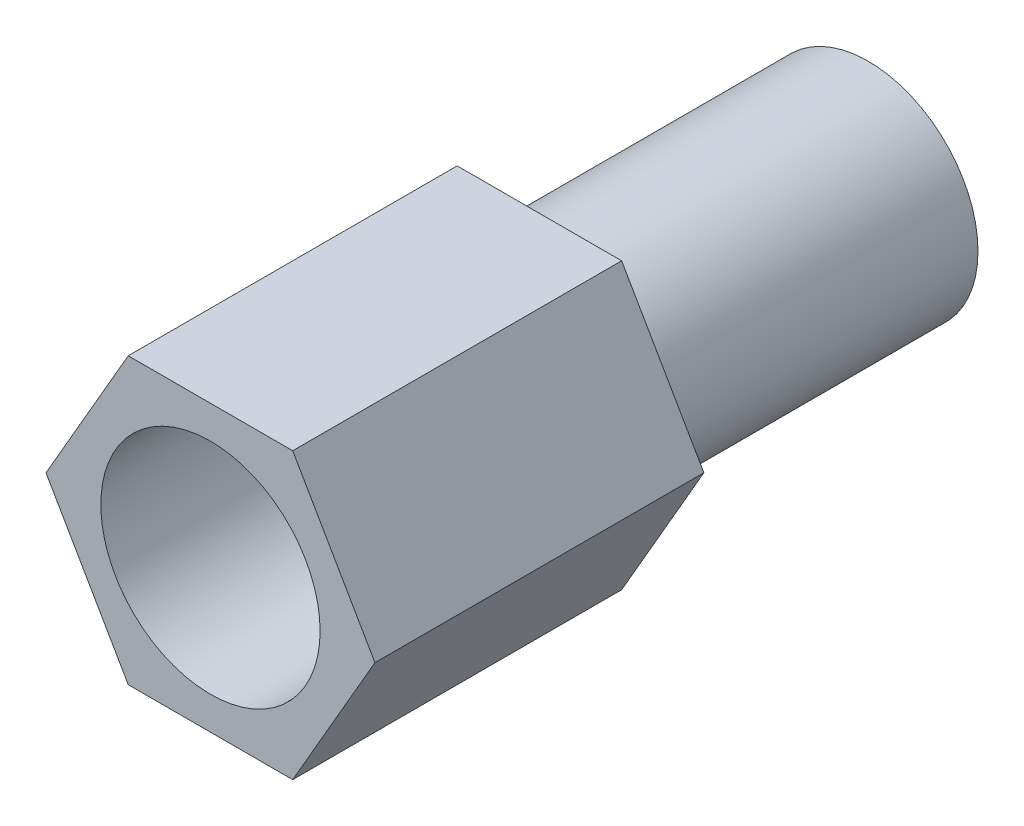
SolidWorks part; units mm, degrees
ref_plane "前视基准面" through (0, 0, 0) normal (0, 0, 1) x (1, 0, 0)
ref_plane "上视基准面" through (0, 0, 0) normal (0, 1, 0) x (1, 0, 0)
ref_plane "右视基准面" through (0, 0, 0) normal (1, 0, 0) x (0, 0, -1)
sketch "草图1" plane through (0, 0, 0) normal (0, 0, 1) x (1, 0, 0)
  line L1 (-1.5, 0) -> (-0.75, -1.299)
  line L2 (-0.75, -1.299) -> (0.75, -1.299)
  line L3 (0.75, -1.299) -> (1.5, 0)
  line L4 (1.5, 0) -> (0.75, 1.299)
  line L5 (0.75, 1.299) -> (-0.75, 1.299)
  line L6 (-0.75, 1.299) -> (-1.5, 0)
  circle A0 centre (0, 0) radius 1.299 construction
  circle A1 centre (0, 0) radius 1
  dimension "D1" = 2
  dimension "D2" = 3
extrude "凸台-拉伸1" add sketch "草图1" along normal blind 3
sketch "草图2" plane through (0, 0, 0) normal (0, 0, 1) x (1, 0, 0)
  circle A0 centre (0, 0) radius 1
extrude "凸台-拉伸2" add sketch "草图2" against normal blind 3 separate body
